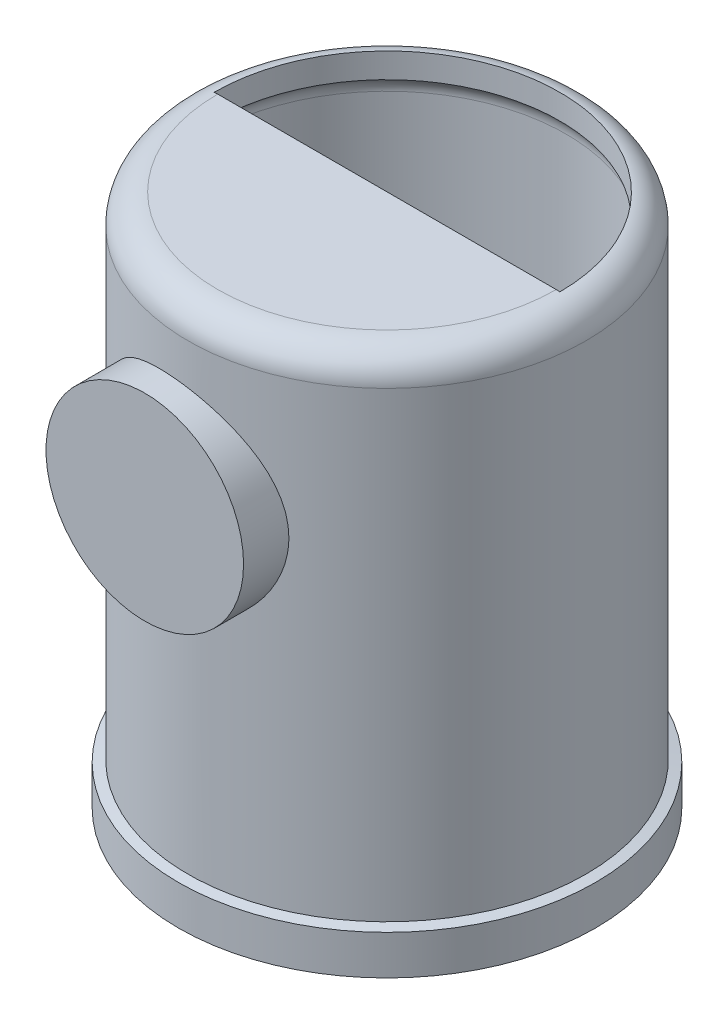
SolidWorks part; units mm, degrees
ref_plane "Front Plane" through (0, 0, 0) normal (0, 0, 1) x (1, 0, 0)
ref_plane "Top Plane" through (0, 0, 0) normal (0, 1, 0) x (1, 0, 0)
ref_plane "Right Plane" through (0, 0, 0) normal (1, 0, 0) x (0, 0, -1)
sketch "Sketch1" plane through (0, 0, 0) normal (0, 0, 1) x (1, 0, 0)
  line L0 (2.7649, 7.8218) -> (2.7649, 58.3592) construction
  line L1 (20.9, 0) -> (23.8716, 0)
  line L2 (23.8716, 0) -> (23.8716, 4)
  line L3 (23.8716, 4) -> (22.9, 4.2367)
  line L4 (22.9, 4.2367) -> (22.9, 51)
  line L6 (20.9, 0) -> (20.9, 15)
  line L7 (18.9, 52) -> (2.7649, 52)
  line L8 (2.7649, 52) -> (2.7649, 54)
  line L9 (20.9, 17) -> (20.9, 50)
  line L10 (20.9, 17) -> (2.7649, 17)
  line L12 (20.9, 15) -> (2.7649, 15)
  line L13 (2.7649, 17) -> (2.7649, 15)
  line L14 (19.9, 54) -> (2.7649, 54)
  arc A1 (20.9, 50) -> (18.9, 52) centre (18.9, 50) ccw
  arc A2 (22.9, 51) -> (19.9, 54) centre (19.9, 51) ccw
  point P11 (22.9, 54)
  dimension "D9" = 2
  dimension "D4" = 3
  dimension "D1" = 2
  dimension "D2" = 4
  dimension "D3" = 1
  dimension "D6" = 2
  dimension "D7" = 2.9716
  dimension "D10" = 2
  dimension "D11" = 15
  dimension "D12" = 35
  dimension "D13" = 37
revolve "Revolve1" add sketch "Sketch1" angle 360 about L0
ref_plane "Plane1" through (0, 4, 0) normal (0, 1, 0) x (1, 0, 0)
sketch "Sketch3" plane through (0, 0, 0) normal (0, 0, 1) x (1, 0, 0)
  point P0 (1.2404, 19.1989)
ref_point "Point1"
ref_plane "Plane2" through (0, 0, 22.9) normal (0, 0, 1) x (1, 0, 0)
sketch "Sketch4" plane through (0, 0, 22.9) normal (0, 0, 1) x (1, 0, 0)
  line L1 (22.9, 51) -> (-17.3702, 51) construction
  circle A1 centre (1.1446, 37) radius 10
  dimension "D1" = 20
  dimension "D2" = 14
extrude "Boss-Extrude2" add sketch "Sketch4" against normal blind 6
ref_plane "Plane3" through (0, 0, 16.9) normal (0, 0, -1) x (-1, 0, 0)
ref_plane "Plane4" through (0, 54, 0) normal (0, 1, 0) x (1, 0, 0)
sketch "Sketch9" plane through (0, 54, 0) normal (0, 1, 0) x (1, 0, 0)
  line L0 (-14.7351, -0.0013) -> (20.2649, -0.0013)
  arc A0 (20.2649, -0.0013) -> (-14.7351, -0.0013) centre (2.7649, -0.0013) ccw
  circle A1 centre (2.7649, 0) radius 17.1351 construction
  dimension "D1" = 35
  dimension "D3" = 17.5
  dimension "D2" = 17.5
extrude "Cut-Extrude2" cut sketch "Sketch9" against normal blind 40
